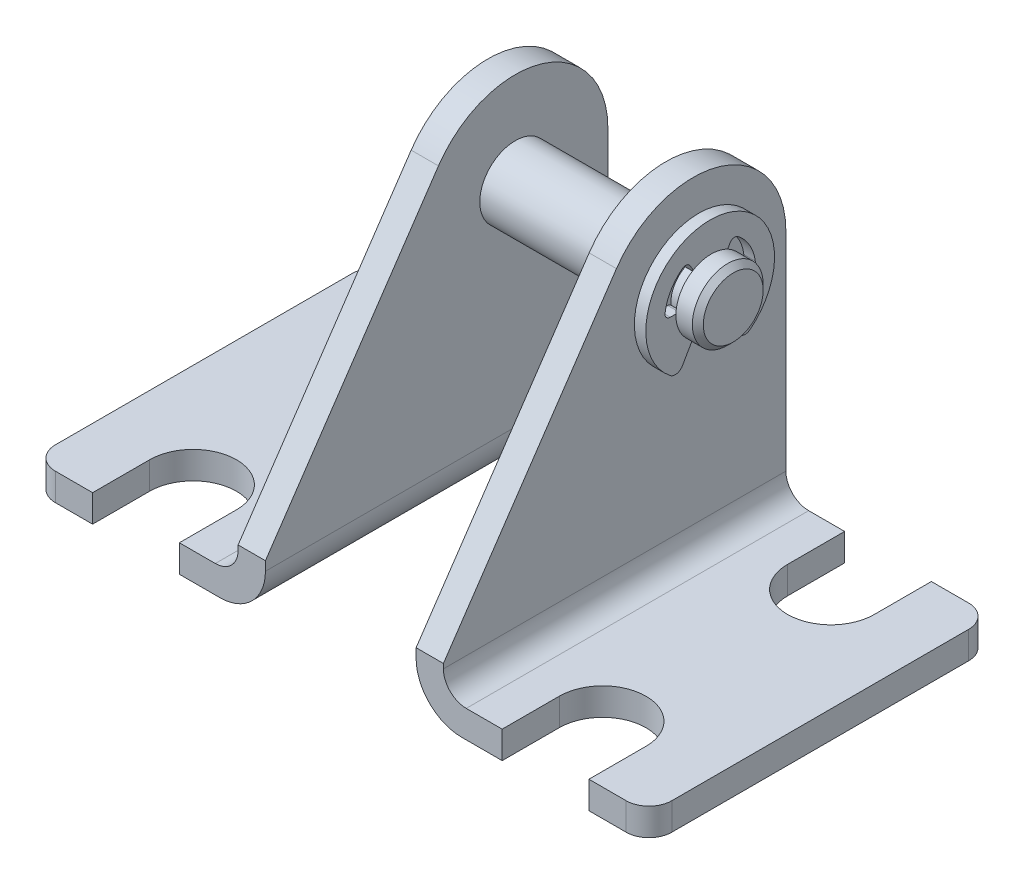
SolidWorks part; units mm, degrees
ref_plane "Front Plane" through (0, 0, 0) normal (0, 0, 1) x (1, 0, 0)
ref_plane "Top Plane" through (0, 0, 0) normal (0, 1, 0) x (1, 0, 0)
ref_plane "Right Plane" through (0, 0, 0) normal (1, 0, 0) x (0, 0, -1)
sketch "Sketch1" plane through (0, 0, 0) normal (0, 1, 0) x (1, 0, 0)
  line L0 (-17.145, 0) -> (17.145, 0) construction
  line L1 (-17.145, 5.1562) -> (-13.8049, 5.1562)
  line L2 (-17.145, 5.1562) -> (-17.145, -13.8938)
  line L3 (-17.145, -13.8938) -> (-13.8049, -13.8938)
  line L4 (17.145, 5.1562) -> (17.145, -13.8938)
  line L5 (-4.191, 5.1562) -> (-4.191, -13.8938)
  line L6 (4.191, 5.1562) -> (4.191, -13.8938)
  line L7 (4.191, 5.1562) -> (8.9789, 5.1562)
  line L8 (4.191, -13.8938) -> (8.9789, -13.8938)
  line L9 (-5.7099, 5.1562) -> (-5.7099, -13.8938) construction
  line L10 (-4.191, 5.1562) -> (4.191, 5.1562) construction
  line L11 (-4.191, -13.8938) -> (4.191, -13.8938) construction
  line L12 (0, 5.1562) -> (0, 0) construction
  line L13 (-13.8049, 1.9812) -> (-13.8049, 5.1562)
  line L14 (-8.9789, 1.9812) -> (-8.9789, 5.1562)
  line L15 (8.9789, 1.9812) -> (8.9789, 5.1562)
  line L16 (13.8049, 1.9812) -> (13.8049, 5.1562)
  line L17 (13.8049, -10.7188) -> (13.8049, -13.8938)
  line L18 (8.9789, -10.7188) -> (8.9789, -13.8938)
  line L19 (-8.9789, -10.7188) -> (-8.9789, -13.8938)
  line L20 (-13.8049, -10.7188) -> (-13.8049, -13.8938)
  line L21 (-8.9789, -13.8938) -> (-4.191, -13.8938)
  line L22 (13.8049, -13.8938) -> (17.145, -13.8938)
  line L23 (13.8049, 5.1562) -> (17.145, 5.1562)
  line L24 (-8.9789, 5.1562) -> (-4.191, 5.1562)
  line L25 (5.7099, 5.1562) -> (5.7099, -13.8938) construction
  arc A0 (-13.8049, 1.9812) -> (-8.9789, 1.9812) centre (-11.3919, 1.9812) ccw
  arc A1 (-8.9789, -10.7188) -> (-13.8049, -10.7188) centre (-11.3919, -10.7188) ccw
  arc A2 (13.8049, -10.7188) -> (8.9789, -10.7188) centre (11.3919, -10.7188) ccw
  arc A3 (8.9789, 1.9812) -> (13.8049, 1.9812) centre (11.3919, 1.9812) ccw
sketch "Sketch2" plane through (0, 0, 0) normal (1, 0, 0) x (0, 0, -1)
  line L0 (-13.8938, 0) -> (5.1562, 0)
  line L1 (0, 14.3637) -> (0, 0) construction
  line L2 (-13.8938, 0) -> (-13.8938, 3.048)
  line L3 (-13.8938, 3.048) -> (-4.2689, 17.2556)
  line L4 (5.1562, 14.3637) -> (5.1562, 0)
  arc A0 (-4.2689, 17.2556) -> (5.1562, 14.3637) centre (0, 14.3637) cw
  circle A1 centre (0, 14.3637) radius 1.9698
  dimension "Pin Dia" = 3.9395
  dimension "D1" = 3.048
  dimension "E" = 19.5199
  dimension "F" = 14.3637
sketch "Sketch3" plane through (0, 0, 0) normal (0, 1, 0) x (1, 0, 0)
  line L12 (8.9789, -13.8938) -> (8.9789, -10.7188)
  line L13 (13.8049, -10.7188) -> (13.8049, -13.8938)
  line L14 (13.8049, -13.8938) -> (17.145, -13.8938)
  line L15 (17.145, -13.8938) -> (17.145, 5.1562)
  line L16 (17.145, 5.1562) -> (13.8049, 5.1562)
  line L17 (13.8049, 5.1562) -> (13.8049, 1.9812)
  line L18 (8.9789, 1.9812) -> (8.9789, 5.1562)
  line L19 (8.9789, 5.1562) -> (4.191, 5.1562)
  line L20 (4.191, 5.1562) -> (4.191, -13.8938)
  line L21 (4.191, -13.8938) -> (8.9789, -13.8938)
  line L22 (8.9789, -13.8938) -> (8.9789, -10.7188)
  line L23 (13.8049, -10.7188) -> (13.8049, -13.8938)
  line L24 (13.8049, -13.8938) -> (17.145, -13.8938)
  line L25 (17.145, -13.8938) -> (17.145, 5.1562)
  line L26 (17.145, 5.1562) -> (13.8049, 5.1562)
  line L27 (13.8049, 5.1562) -> (13.8049, 1.9812)
  line L28 (8.9789, 1.9812) -> (8.9789, 5.1562)
  line L29 (8.9789, 5.1562) -> (4.191, 5.1562)
  line L30 (4.191, 5.1562) -> (4.191, -13.8938)
  line L31 (4.191, -13.8938) -> (8.9789, -13.8938)
  line L32 (-17.145, -13.8938) -> (-13.8049, -13.8938)
  line L33 (-17.145, 5.1562) -> (-17.145, -13.8938)
  line L34 (-13.8049, 5.1562) -> (-17.145, 5.1562)
  line L35 (-13.8049, 1.9812) -> (-13.8049, 5.1562)
  line L36 (-8.9789, 5.1562) -> (-8.9789, 1.9812)
  line L37 (-4.191, 5.1562) -> (-8.9789, 5.1562)
  line L38 (-4.191, -13.8938) -> (-4.191, 5.1562)
  line L39 (-8.9789, -13.8938) -> (-4.191, -13.8938)
  line L40 (-8.9789, -10.7188) -> (-8.9789, -13.8938)
  line L41 (-13.8049, -13.8938) -> (-13.8049, -10.7188)
  line L42 (-17.145, -13.8938) -> (-13.8049, -13.8938)
  line L43 (-17.145, 5.1562) -> (-17.145, -13.8938)
  line L44 (-13.8049, 5.1562) -> (-17.145, 5.1562)
  line L45 (-13.8049, 1.9812) -> (-13.8049, 5.1562)
  line L46 (-8.9789, 5.1562) -> (-8.9789, 1.9812)
  line L47 (-4.191, 5.1562) -> (-8.9789, 5.1562)
  line L48 (-4.191, -13.8938) -> (-4.191, 5.1562)
  line L49 (-8.9789, -13.8938) -> (-4.191, -13.8938)
  line L50 (-8.9789, -10.7188) -> (-8.9789, -13.8938)
  line L51 (-13.8049, -13.8938) -> (-13.8049, -10.7188)
  arc A2 (13.8049, -10.7188) -> (8.9789, -10.7188) centre (11.3919, -10.7188) ccw
  arc A3 (8.9789, 1.9812) -> (13.8049, 1.9812) centre (11.3919, 1.9812) ccw
  arc A4 (13.8049, -10.7188) -> (8.9789, -10.7188) centre (11.3919, -10.7188) ccw
  arc A5 (8.9789, 1.9812) -> (13.8049, 1.9812) centre (11.3919, 1.9812) ccw
  arc A6 (-13.8049, 1.9812) -> (-8.9789, 1.9812) centre (-11.3919, 1.9812) ccw
  arc A7 (-8.9789, -10.7188) -> (-13.8049, -10.7188) centre (-11.3919, -10.7188) ccw
  arc A8 (-13.8049, 1.9812) -> (-8.9789, 1.9812) centre (-11.3919, 1.9812) ccw
  arc A9 (-8.9789, -10.7188) -> (-13.8049, -10.7188) centre (-11.3919, -10.7188) ccw
  dimension "D1" = 0
  dimension "D2" = 0
extrude "Boss-Extrude1" add sketch "Sketch3" along normal blind 1.5189
sketch "Sketch4" plane through (-4.191, 0, 0) normal (1, 0, 0) x (0, 0, -1)
  line L6 (-13.8938, 0) -> (5.1562, 0)
  line L7 (5.1562, 0) -> (5.1562, 14.3637)
  line L8 (-4.2689, 17.2556) -> (-13.8938, 3.048)
  line L12 (-13.8938, 3.048) -> (-13.8938, 0)
  line L13 (-13.8938, 0) -> (5.1562, 0)
  line L14 (5.1562, 0) -> (5.1562, 14.3637)
  line L15 (-4.2689, 17.2556) -> (-13.8938, 3.048)
  line L16 (-13.8938, 3.048) -> (-13.8938, 0)
  circle A1 centre (0, 14.3637) radius 1.9698
  circle A3 centre (0, 14.3637) radius 1.9698
  arc A5 (5.1562, 14.3637) -> (-4.2689, 17.2556) centre (0, 14.3637) ccw
  arc A6 (5.1562, 14.3637) -> (-4.2689, 17.2556) centre (0, 14.3637) ccw
  dimension "D1" = 0
  dimension "D2" = 0
extrude "Boss-Extrude2" add sketch "Sketch4" against normal up to vertex (1.5189 mm away) up to point (-5.7099, 0, -5.1562)
sketch "Sketch5" plane through (4.191, 0, 0) normal (-1, 0, 0) x (0, 0, 1)
  line L4 (-5.1562, 0) -> (13.8938, 0)
  line L5 (-5.1562, 14.3637) -> (-5.1562, 0)
  line L6 (13.8938, 3.048) -> (4.2689, 17.2556)
  line L7 (13.8938, 0) -> (13.8938, 3.048)
  line L8 (-5.1562, 0) -> (13.8938, 0)
  line L9 (-5.1562, 14.3637) -> (-5.1562, 0)
  line L10 (13.8938, 3.048) -> (4.2689, 17.2556)
  line L11 (13.8938, 0) -> (13.8938, 3.048)
  circle A1 centre (0, 14.3637) radius 1.9698
  circle A2 centre (0, 14.3637) radius 1.9698
  arc A3 (4.2689, 17.2556) -> (-5.1562, 14.3637) centre (0, 14.3637) ccw
  arc A4 (4.2689, 17.2556) -> (-5.1562, 14.3637) centre (0, 14.3637) ccw
  dimension "D1" = 0
  dimension "D2" = 0
extrude "Boss-Extrude3" add sketch "Sketch5" against normal up to vertex (1.5189 mm away) up to point (5.7099, 0, -5.1562)
fillet "Fillet1" radius 1.27 3 edges at (-5.7099, 1.5189, 4.3688) (-17.145, 0.7595, -5.1562) (-17.145, 0.7595, 13.8938)
fillet "Fillet2" radius 2.54 1 edges at (-4.191, 0, 4.3688)
fillet "Fillet3" radius 1.27 3 edges at (5.7099, 1.5189, 4.3688) (17.145, 0.7595, -5.1562) (17.145, 0.7595, 13.8938)
fillet "Fillet4" radius 2.54 1 edges at (4.191, 0, 4.3688)
sketch "Sketch6" plane through (0, 0, 0) normal (0, 0, 1) x (1, 0, 0)
  line L0 (0, 14.3637) -> (0, 16.3335) construction
  line L1 (-7.6327, 16.3335) -> (-6.7183, 16.3335)
  line L2 (-7.9375, 16.0287) -> (-7.9375, 14.3637)
  line L3 (-7.9375, 14.3637) -> (7.9375, 14.3637)
  line L4 (7.9375, 16.0287) -> (7.9375, 14.3637)
  line L8 (-7.9375, 16.0287) -> (-7.6327, 16.3335)
  line L9 (-6.7183, 16.3335) -> (-6.7183, 15.8496)
  line L10 (-6.7183, 15.8496) -> (-5.9563, 15.8496)
  line L11 (-5.9563, 15.8496) -> (-5.9563, 16.3335)
  line L12 (5.9563, 16.3335) -> (5.9563, 15.8496)
  line L13 (5.9563, 15.8496) -> (6.7183, 15.8496)
  line L14 (6.7183, 15.8496) -> (6.7183, 16.3335)
  line L15 (7.6327, 16.3335) -> (7.9375, 16.0287)
  line L16 (-5.9563, 16.3335) -> (5.9563, 16.3335)
  line L17 (6.7183, 16.3335) -> (7.6327, 16.3335)
  line L18 (-7.9375, 16.0287) -> (-7.9375, 16.3335) construction
  line L19 (-7.9375, 16.3335) -> (-7.6327, 16.3335) construction
  line L20 (-6.7183, 16.3335) -> (-5.9563, 16.3335) construction
  line L21 (5.9563, 16.3335) -> (6.7183, 16.3335) construction
  line L22 (7.6327, 16.3335) -> (7.9375, 16.3335) construction
  line L23 (7.9375, 16.3335) -> (7.9375, 16.0287) construction
  line L24 (-7.9375, 14.3637) -> (7.9375, 14.3637) construction
  line L25 (-6.3373, 15.8496) -> (-6.3373, 14.3637) construction
  point P22 (-6.3373, 14.3637)
  dimension "Gap OD" = 2.9718
  dimension "Gap" = 0.762
  dimension "Chamfer" = 0.3048
  dimension "Pin Lg." = 15.875
  dimension "Center Lg." = 11.9126
revolve "Revolve1" add sketch "Sketch6" angle 360 about L24
ref_plane "Plane1" through (-6.3373, 0, 0) normal (1, 0, 0) x (0, 0, -1)
sketch "Sketch7" plane through (-6.3373, 0, 0) normal (1, 0, 0) x (0, 0, -1)
  line L0 (0, 14.3637) -> (0, 15.8496) construction
  line L1 (0, 14.3637) -> (0.8637, 15.8597) construction
  line L2 (0.8637, 15.8597) -> (1.1076, 16.2821)
  line L3 (0, 14.3637) -> (1.7274, 14.3637) construction
  line L4 (1.7274, 14.3637) -> (2.2152, 14.3637)
  line L5 (0, 14.3637) -> (0.7429, 13.0769) construction
  line L6 (0.8637, 12.8677) -> (1.5508, 11.6776)
  line L7 (-0.8637, 12.8677) -> (-1.5508, 11.6776)
  line L8 (0, 14.3637) -> (-0.7429, 13.0769) construction
  line L9 (0, 15.8496) -> (0, 16.8974) construction
  line L10 (0, 16.8974) -> (0, 17.9451) construction
  line L11 (-1.7274, 14.3637) -> (-2.2152, 14.3637)
  line L12 (-0.8637, 15.8597) -> (-1.1076, 16.2821)
  circle A0 centre (0, 14.3637) radius 1.4859 construction
  circle A1 centre (0, 14.3637) radius 3.5814 construction
  arc A2 (2.511, 14.702) -> (1.5485, 16.3691) centre (0, 14.3637) ccw
  arc A3 (0.5423, 15.7471) -> (-0.5423, 15.7471) centre (0, 14.3637) ccw
  arc A4 (2.2154, 11.5497) -> (-2.2154, 11.5497) centre (0, 14.3637) ccw
  arc A5 (0.927, 13.2024) -> (1.4692, 14.1416) centre (0, 14.3637) ccw
  circle A6 centre (0, 14.3637) radius 2.5336 construction
  arc A7 (1.5508, 11.6776) -> (2.2154, 11.5497) centre (1.9385, 11.9015) ccw
  arc A8 (-1.5508, 11.6776) -> (-2.2154, 11.5497) centre (-1.9385, 11.9015) cw
  arc A9 (1.5485, 16.3691) -> (1.1076, 16.2821) centre (1.3661, 16.1329) ccw
  arc A10 (2.511, 14.702) -> (2.2152, 14.3637) centre (2.2152, 14.6622) cw
  arc A11 (0.8637, 12.8677) -> (0.927, 13.2024) centre (1.0899, 12.9983) cw
  arc A12 (0.5423, 15.7471) -> (0.8637, 15.8597) centre (0.6376, 15.9903) ccw
  arc A13 (1.7274, 14.3637) -> (1.4692, 14.1416) centre (1.7274, 14.1026) ccw
  arc A14 (-0.8637, 12.8677) -> (-0.927, 13.2024) centre (-1.0899, 12.9983) ccw
  arc A15 (-0.927, 13.2024) -> (-1.4692, 14.1416) centre (0, 14.3637) cw
  arc A16 (-1.7274, 14.3637) -> (-1.4692, 14.1416) centre (-1.7274, 14.1026) cw
  arc A17 (-2.511, 14.702) -> (-2.2152, 14.3637) centre (-2.2152, 14.6622) ccw
  arc A18 (-2.511, 14.702) -> (-1.5485, 16.3691) centre (0, 14.3637) cw
  arc A19 (-1.5485, 16.3691) -> (-1.1076, 16.2821) centre (-1.3661, 16.1329) cw
  arc A20 (-0.5423, 15.7471) -> (-0.8637, 15.8597) centre (-0.6376, 15.9903) cw
  point P18 (1.7907, 11.2621)
  point P21 (-1.7907, 11.2621)
  point P26 (2.5336, 14.3637)
  dimension "D2" = 0.4477
  dimension "D4" = 0.2984
  dimension "D5" = 0.2611
  dimension "D1" = 30
  dimension "D3" = 30
extrude "Boss-Extrude5" add sketch "Sketch7" along normal mid plane 0.635 separate body
mirror "Mirror1" about plane through (0, 0, 0) normal (1, 0, 0) of bodies 112
equation "\"D1@Boss-Extrude1\" = \"D@Sketch1\""
equation "\"D1@Fillet2\" = \"D1@Fillet1\" * 2"
equation "\"D1@Fillet3\" = \"D1@Fillet1\""
equation "\"D1@Fillet4\" = \"D1@Fillet2\""
equation "\"D2@Sketch7\" = \"OD@Sketch7\" * 1 / 16"
equation "\"D4@Sketch7\" = \"D2@Sketch7\" * 2 / 3"
equation "\"D5@Sketch7\" = \"D4@Sketch7\" * 7 / 8"
